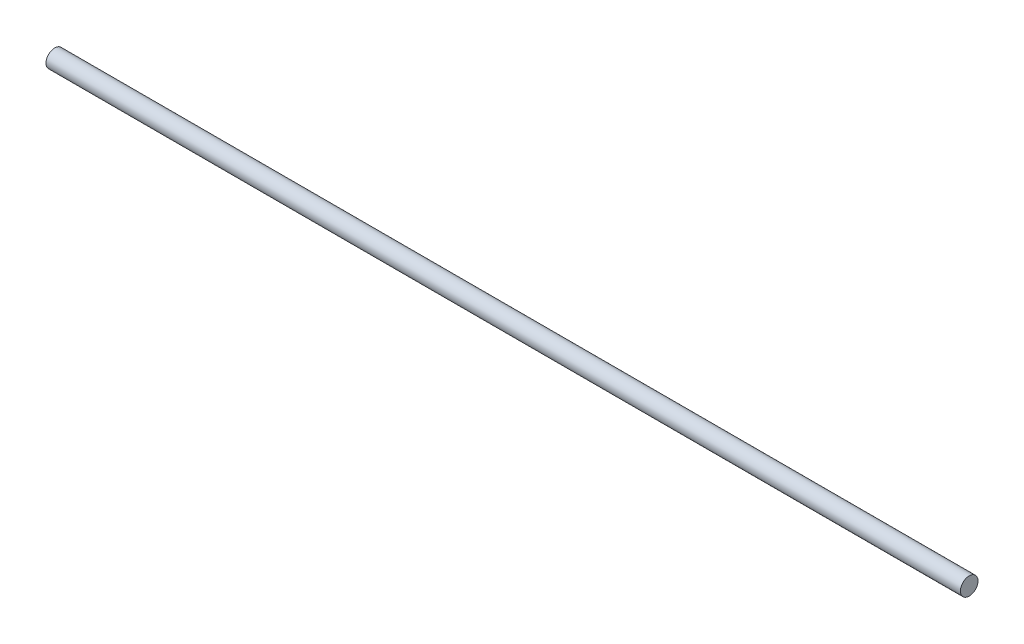
SolidWorks part; units mm, degrees
material "Zoltek Panex 33"
ref_plane "Front Plane" through (0, 0, 0) normal (0, 0, 1) x (1, 0, 0)
ref_plane "Top Plane" through (0, 0, 0) normal (0, 1, 0) x (1, 0, 0)
ref_plane "Right Plane" through (0, 0, 0) normal (1, 0, 0) x (0, 0, -1)
sketch "Sketch1" plane through (0, 0, 0) normal (1, 0, 0) x (0, 0, -1)
  circle A0 centre (0, 0) radius 9
  dimension "D1" = 18
extrude "Boss-Extrude1" add sketch "Sketch1" along normal mid plane 936
